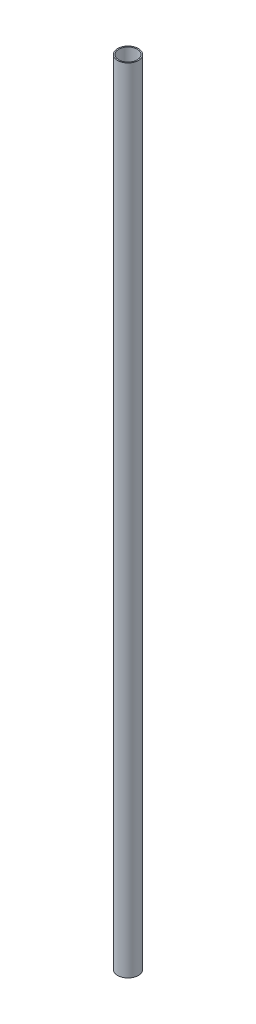
SolidWorks part; units mm, degrees
material "Custom Plastic"
ref_plane "X-Y Datum" through (0, 0, 0) normal (0, 0, 1) x (1, 0, 0)
ref_plane "X-Z Datum" through (0, 0, 0) normal (0, 1, 0) x (1, 0, 0)
ref_plane "Y-Z Datum" through (0, 0, 0) normal (1, 0, 0) x (0, 0, -1)
ref_point "Middle point"
sketch "Sketch2" plane through (0, 0, 0) normal (0, 1, 0) x (1, 0, 0)
  circle A0 centre (0, 0) radius 5.6134
  circle A1 centre (0, 0) radius 6.35
  dimension "D1" = 12.7
  dimension "D2" = 11.2268
extrude "Tube Stock - Extrude" add sketch "Sketch2" along normal blind 241.3 and the other way blind 241.3
equation "\"Torsion Tube Stock Outer Diameter\" = 0.5in"
equation "\"Torsion Tube Stock Wall Thickness\"= 0.058"
equation "\"D1@Sketch2\"= \"Torsion Tube Stock Outer Diameter\""
equation "\"D2@Sketch2\"= \"Torsion Tube Stock Outer Diameter\" - \"Torsion Tube Stock Wall Thickness\""
equation "\"Torsion Tube Stock Length\"= 19in"
equation "\"D1@Tube Stock - Extrude\"=\"Torsion Tube Stock Length\"/2"
equation "\"D2@Tube Stock - Extrude\"=\"Torsion Tube Stock Length\"/2"
